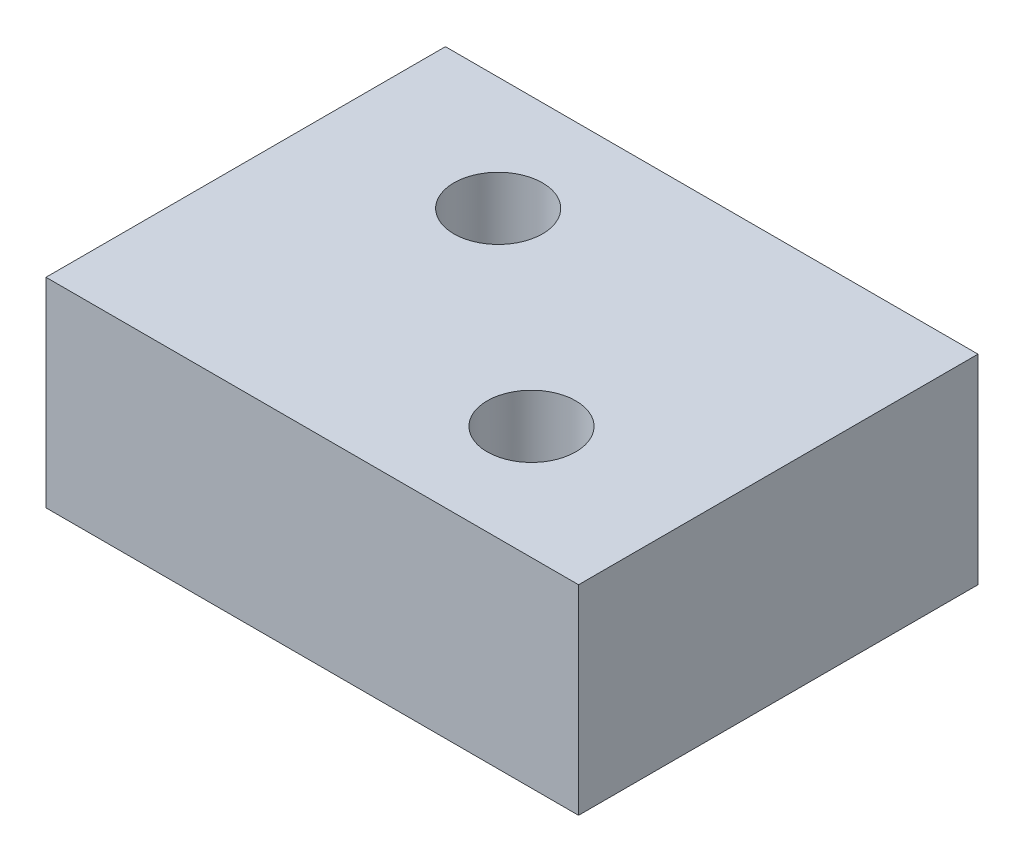
SolidWorks part; units mm, degrees
material "PLA"
ref_plane "Front Plane" through (0, 0, 0) normal (0, 0, 1) x (1, 0, 0)
ref_plane "Top Plane" through (0, 0, 0) normal (0, 1, 0) x (1, 0, 0)
ref_plane "Right Plane" through (0, 0, 0) normal (1, 0, 0) x (0, 0, -1)
sketch "Sketch2" plane through (0, 0, 0) normal (0, 1, 0) x (1, 0, 0)
  line L1 (-20, -15) -> (20, -15)
  line L2 (-20, -15) -> (-20, 15)
  line L3 (-20, 15) -> (20, 15)
  line L4 (20, -15) -> (20, 15)
  line L5 (-20, -15) -> (20, 15) construction
  line L6 (-20, 15) -> (20, -15) construction
  point P0 (0, 0)
  dimension "D1" = 40
  dimension "D2" = 30
extrude "Boss-Extrude1" add sketch "Sketch2" along normal blind 10
sketch "Sketch3" plane through (0, 0, 0) normal (0, -1, 0) x (-1, 0, 0)
  line L0 (20, -15) -> (-20, 15) construction
  line L1 (-20, -15) -> (20, 15) construction
  line L2 (0, -15) -> (0, 15) construction
  line L3 (20, -15) -> (-20, -15) construction
  line L4 (-20, 15) -> (20, 15) construction
  line L5 (20, 0) -> (-20, 0) construction
  line L6 (20, 15) -> (20, -15) construction
  line L7 (-20, -15) -> (-20, 15) construction
  circle A0 centre (-13.3333, -10) radius 2
  circle A1 centre (13.3333, -10) radius 2
  circle A2 centre (-13.3333, 10) radius 2
  circle A3 centre (13.3333, 10) radius 2
  dimension "D1" = 4
  dimension "D2" = 5
extrude "Cut-Extrude1" cut sketch "Sketch3" against normal blind 5
sketch "Sketch4" plane through (0, 10, 0) normal (0, 1, 0) x (1, 0, 0)
  line L0 (20, -15) -> (20, 15) construction
  line L1 (-20, -15) -> (20, -15) construction
  line L2 (-20, 15) -> (-20, -15) construction
  line L4 (7.9286, -6.465) -> (7.9286, 6.4636) construction
  circle A0 centre (7.9286, -6.465) radius 4.8125
  circle A1 centre (-7.5, 6.4636) radius 4.8125
  dimension "D1" = 9.625
  dimension "D6" = 9.625
  dimension "D2" = 12.0714
  dimension "D3" = 8.535
  dimension "D4" = 12.5
  dimension "D5" = 12.9286
extrude "Cut-Extrude2" cut sketch "Sketch4" against normal blind 4
sketch "Sketch8" plane through (0, 10, 0) normal (0, 1, 0) x (1, 0, 0)
  line L1 (-20, -15) -> (20, -15)
  line L2 (-20, -15) -> (-20, 15)
  line L3 (-20, 15) -> (20, 15)
  line L4 (20, -15) -> (20, 15)
extrude "Boss-Extrude2" add sketch "Sketch8" along normal blind 5
sketch "Sketch7" plane through (0, 6, 0) normal (0, 1, 0) x (1, 0, 0)
  circle A0 centre (7.9286, -6.465) radius 3.325
  circle A1 centre (-7.5, 6.4636) radius 3.325
  dimension "D1" = 6.65
  dimension "D2" = 6.65
extrude "Cut-Extrude3" cut sketch "Sketch7" against normal blind 1 and the other way through all
